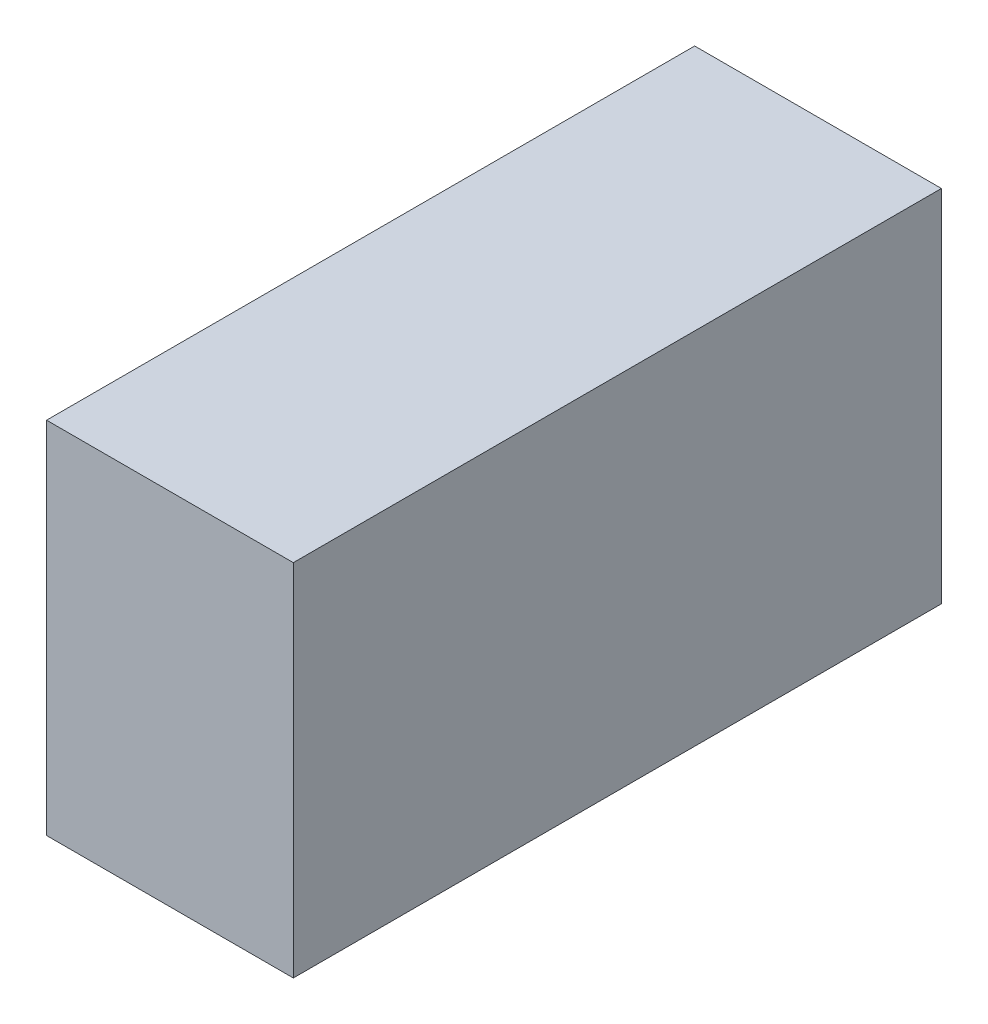
SolidWorks part; units mm, degrees
ref_plane "Front Plane" through (0, 0, 0) normal (0, 0, 1) x (1, 0, 0)
ref_plane "Top Plane" through (0, 0, 0) normal (0, 1, 0) x (1, 0, 0)
ref_plane "Right Plane" through (0, 0, 0) normal (1, 0, 0) x (0, 0, -1)
sketch "Sketch1" plane through (0, 0, 0) normal (0, 0, 1) x (1, 0, 0)
  line L1 (-36.5113, 43.9893) -> (46.4887, 43.9893)
  line L2 (-36.5113, 43.9893) -> (-36.5113, -77.0107)
  line L3 (-36.5113, -77.0107) -> (46.4887, -77.0107)
  line L4 (46.4887, 43.9893) -> (46.4887, -77.0107)
  dimension "D1" = 121
  dimension "D2" = 83
extrude "Boss-Extrude1" add sketch "Sketch1" along normal blind 218
